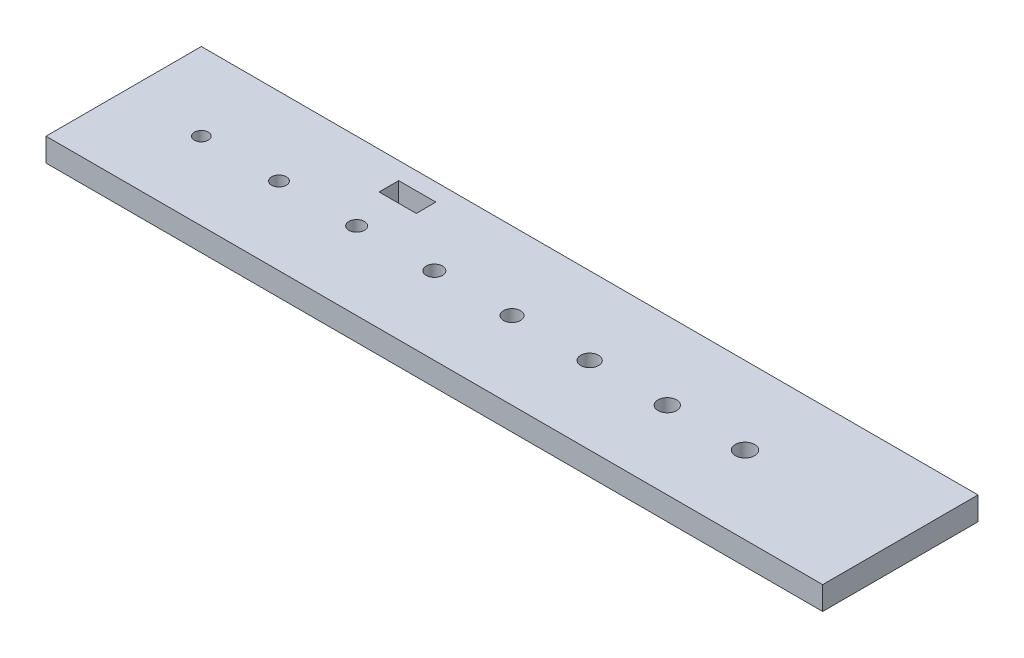
SolidWorks part; units mm, degrees
ref_plane "Front Plane" through (0, 0, 0) normal (0, 0, 1) x (1, 0, 0)
ref_plane "Top Plane" through (0, 0, 0) normal (0, 1, 0) x (1, 0, 0)
ref_plane "Right Plane" through (0, 0, 0) normal (1, 0, 0) x (0, 0, -1)
sketch "Sketch1" plane through (0, 0, 0) normal (0, 1, 0) x (1, 0, 0)
  line L1 (0, 0) -> (100, 0)
  line L2 (0, 0) -> (0, -20)
  line L3 (0, -20) -> (100, -20)
  line L4 (100, 0) -> (100, -20)
  dimension "D1" = 100
  dimension "D2" = 20
extrude "Boss-Extrude1" add sketch "Sketch1" along normal blind 3
sketch "Sketch2" plane through (0, 3, 0) normal (0, 1, 0) x (1, 0, 0)
  line L0 (0, -10) -> (100, -10)
  line L1 (0, 0) -> (0, -20) construction
  line L2 (100, -20) -> (100, 0) construction
  line L3 (100, 0) -> (0, 0) construction
  line L5 (27.6629, -2.2509) -> (32.448, -2.2509)
  line L6 (27.6629, -2.2509) -> (27.6629, -4.774)
  line L7 (27.6629, -4.774) -> (32.448, -4.774)
  line L8 (32.448, -2.2509) -> (32.448, -4.774)
  circle A0 centre (10, -10) radius 0.9
  circle A1 centre (30, -10) radius 1
  circle A2 centre (40, -10) radius 1.05
  circle A3 centre (50, -10) radius 1.1
  circle A4 centre (60, -10) radius 1.15
  circle A5 centre (20, -10) radius 0.95
  circle A6 centre (70, -10) radius 1.2
  circle A7 centre (80, -10) radius 1.25
  dimension "D2" = 1.8
  dimension "D3" = 2
  dimension "D4" = 2.1
  dimension "D5" = 2.2
  dimension "D6" = 2.3
  dimension "D7" = 1.9
  dimension "D8" = 2.5
  dimension "D9" = 2.4
  dimension "D1" = 10
  dimension "D10" = 10
  dimension "D11" = 10
  dimension "D12" = 10
  dimension "D13" = 10
  dimension "D14" = 10
  dimension "D15" = 10
  dimension "D16" = 10
  dimension "D17" = 10
extrude "Cut-Extrude1" cut sketch "Sketch2" against normal blind 3 contours L0 A2 | L0 A2 | L0 A1 | L0 A1 | L8 L5 L6 L7 | L0 A5 | L0 A5 | L0 A6 | L0 A6 | L0 A7 | L0 A3 | L0 A3 | L0 A0 | L0 A0 | L0 A4 | L0 A4 | L0 A7
